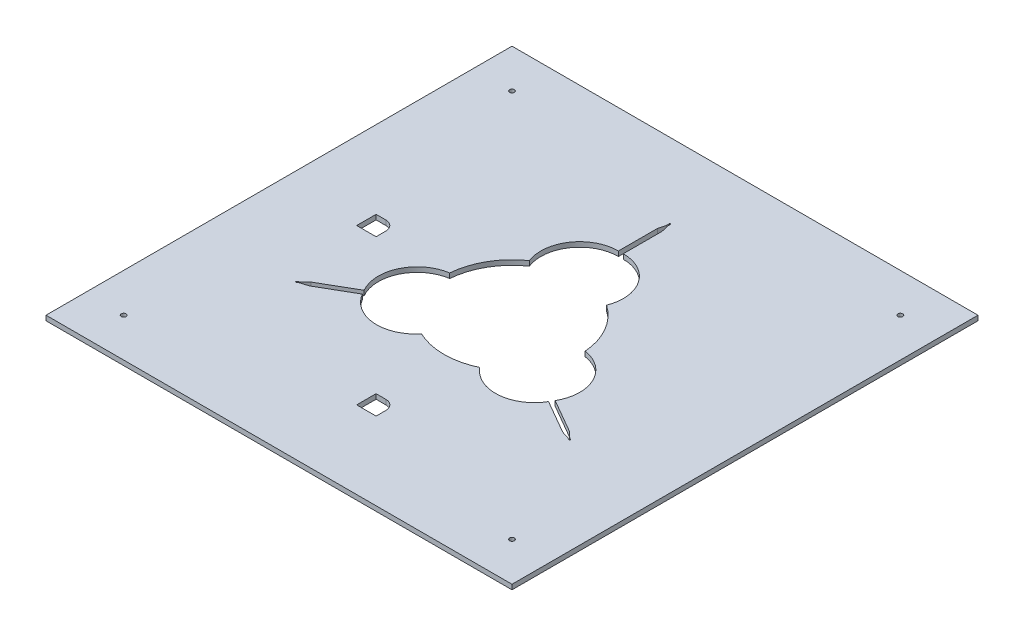
SolidWorks part; units mm, degrees
ref_plane "Front Plane" through (0, 0, 0) normal (0, 0, 1) x (1, 0, 0)
ref_plane "Top Plane" through (0, 0, 0) normal (0, 1, 0) x (1, 0, 0)
ref_plane "Right Plane" through (0, 0, 0) normal (1, 0, 0) x (0, 0, -1)
sketch "Sketch1" plane through (0, 0, 0) normal (0, 1, 0) x (1, 0, 0)
  line L1 (-304.8, -304.8) -> (304.8, -304.8)
  line L2 (-304.8, -304.8) -> (-304.8, 304.8)
  line L3 (-304.8, 304.8) -> (304.8, 304.8)
  line L4 (304.8, -304.8) -> (304.8, 304.8)
  line L5 (0, 304.8) -> (0, -304.8) construction
  line L6 (-304.8, 0) -> (304.8, 0) construction
  point P0 (0, 0)
  dimension "D1" = 609.6
  dimension "D2" = 609.6
extrude "Boss-Extrude1" add sketch "Sketch1" along normal blind 6.35 contours L2 L3 L4 L1
sketch "Sketch3" plane through (0, 0, 0) normal (0, 1, 0) x (1, 0, 0)
  line L0 (0, 0) -> (0, 332.7806) construction
  line L1 (0, 0) -> (-286.8222, -165.5969) construction
  line L2 (0, 0) -> (289.9079, -167.3784) construction
  line L3 (-3.175, 193.2547) -> (-3.175, 142.4547)
  line L4 (-50.4923, 73.1692) -> (50.4923, 73.1692) construction
  line L5 (-3.175, 193.2547) -> (-1.5875, 199.6047)
  line L6 (1.5875, 199.6047) -> (3.175, 193.2547)
  line L7 (3.175, 193.2547) -> (3.175, 142.4547)
  line L9 (-1.5875, 199.6047) -> (1.5875, 199.6047) construction
  line L10 (1.5875, 199.6047) -> (0.7937, 202.7797)
  line L11 (-1.5875, 199.6047) -> (-0.7937, 202.7797)
  line L12 (-0.7937, 202.7797) -> (0.7937, 202.7797) construction
  line L13 (-0.7937, 202.7797) -> (-0.7937, 206.5897)
  line L14 (168.951, -93.8777) -> (124.9569, -68.4777)
  line L15 (0.7937, 206.5897) -> (0.7937, 202.7797)
  line L16 (168.951, -93.8777) -> (173.6565, -98.4275)
  line L17 (173.6565, -98.4275) -> (176.0092, -100.7024)
  line L18 (176.0092, -100.7024) -> (179.3088, -102.6074)
  line L19 (178.515, -103.9823) -> (175.2155, -102.0773)
  line L20 (-3.175, 142.4547) -> (3.175, 142.4547) construction
  line L22 (172.069, -101.1772) -> (175.2155, -102.0773)
  line L25 (172.069, -101.1772) -> (165.776, -99.377)
  line L26 (165.776, -99.377) -> (121.7819, -73.977)
  line L27 (-165.776, -99.377) -> (-121.7819, -73.977)
  line L28 (-165.776, -99.377) -> (-172.069, -101.1772)
  line L29 (-172.069, -101.1772) -> (-175.2155, -102.0773)
  line L30 (-175.2155, -102.0773) -> (-178.515, -103.9823)
  line L31 (-179.3088, -102.6074) -> (-176.0092, -100.7024)
  line L32 (-173.6565, -98.4275) -> (-176.0092, -100.7024)
  line L33 (-173.6565, -98.4275) -> (-168.951, -93.8777)
  line L34 (-168.951, -93.8777) -> (-124.9569, -68.4777)
  arc A1 (-3.175, 142.4547) -> (-50.4923, 73.1692) centre (-3.175, 91.6547) ccw
  arc A2 (3.175, 142.4547) -> (50.4923, 73.1692) centre (3.175, 91.6547) cw
  arc A3 (-50.4923, 73.1692) -> (-88.6126, 7.143) centre (0, 0) ccw
  arc A9 (0.7937, 206.5897) -> (-0.7937, 206.5897) centre (0, 206.5897) ccw
  arc A10 (124.9569, -68.4777) -> (88.6126, 7.143) centre (80.9628, -43.0777) ccw
  arc A15 (178.515, -103.9823) -> (179.3088, -102.6074) centre (178.9119, -103.2948) ccw
  arc A16 (121.7819, -73.977) -> (38.1203, -80.3122) centre (77.7878, -48.577) cw
  arc A17 (-121.7819, -73.977) -> (-38.1203, -80.3122) centre (-77.7878, -48.577) ccw
  arc A18 (-179.3088, -102.6074) -> (-178.515, -103.9823) centre (-178.9119, -103.2948) ccw
  arc A19 (-124.9569, -68.4777) -> (-88.6126, 7.143) centre (-80.9628, -43.0777) cw
  arc A21 (-38.1203, -80.3122) -> (38.1203, -80.3122) centre (0, 0) ccw
  arc A24 (88.6126, 7.143) -> (50.4923, 73.1692) centre (0, 0) ccw
  point P3 (0, 169.3508)
  point P17 (0, 88.9)
  point P33 (0, 0)
  point P34 (0, 0)
  point P62 (0, 0)
  dimension "D6" = 88.9
  dimension "D7" = 50.8
  dimension "D11" = 6.35
  dimension "D12" = 110.7047
  dimension "D14" = 3.81
  dimension "D16" = 88.9
  dimension "D10" = 100.9846
  dimension "D2" = 120
  dimension "D3" = 120
  dimension "D4" = 6.35
  dimension "D5" = 50.8
  dimension "D8" = 3.175
  dimension "D9" = 6.35
  dimension "D13" = 1.5875
  dimension "D17" = 3.175
  dimension "D15" = 3
extrude "Cut-Extrude2" cut sketch "Sketch3" along normal through all
sketch "Sketch4" plane through (0, 0, 0) normal (0, 1, 0) x (1, 0, 0)
  line L0 (0, 0) -> (-203.2, 0) construction
  line L1 (0, 0) -> (0, -203.2) construction
  line L3 (0, -203.2) -> (25.4, -203.2)
  line L4 (0, -203.2) -> (0, -177.8)
  line L5 (0, -177.8) -> (25.4, -177.8)
  line L6 (25.4, -203.2) -> (25.4, -177.8)
  line L7 (-203.2, 0) -> (-177.8, 0)
  line L8 (-203.2, 0) -> (-203.2, 25.4)
  line L9 (-203.2, 25.4) -> (-177.8, 25.4)
  line L10 (-177.8, 0) -> (-177.8, 25.4)
  dimension "D1" = 203.2
  dimension "D2" = 203.2
  dimension "D3" = 25.4
  dimension "D4" = 25.4
  dimension "D5" = 25.4
  dimension "D6" = 25.4
extrude "Cut-Extrude8" cut sketch "Sketch4" along normal through all
fillet "Fillet4" radius 12.7 1 edges at (-177.8, 3.175, -25.4)
fillet "Fillet5" radius 12.7 1 edges at (25.4, 3.175, 177.8)
sketch "Sketch5" plane through (0, 6.35, 0) normal (0, 1, 0) x (1, 0, 0)
  line L1 (-254, -254) -> (254, -254) construction
  line L2 (-254, -254) -> (-254, 254) construction
  line L3 (-254, 254) -> (254, 254) construction
  line L4 (254, -254) -> (254, 254) construction
  line L5 (0, 254) -> (0, -254) construction
  line L6 (-254, 0) -> (254, 0) construction
  circle A0 centre (-254, 254) radius 3.175
  circle A1 centre (254, 254) radius 3.175
  circle A2 centre (254, -254) radius 3.175
  circle A3 centre (-254, -254) radius 3.175
  point P0 (0, 0)
  dimension "D3" = 6.35
  dimension "D1" = 508
  dimension "D2" = 508
  dimension "D4" = 2
  dimension "D5" = 2
extrude "Cut-Extrude9" cut sketch "Sketch5" against normal through all
